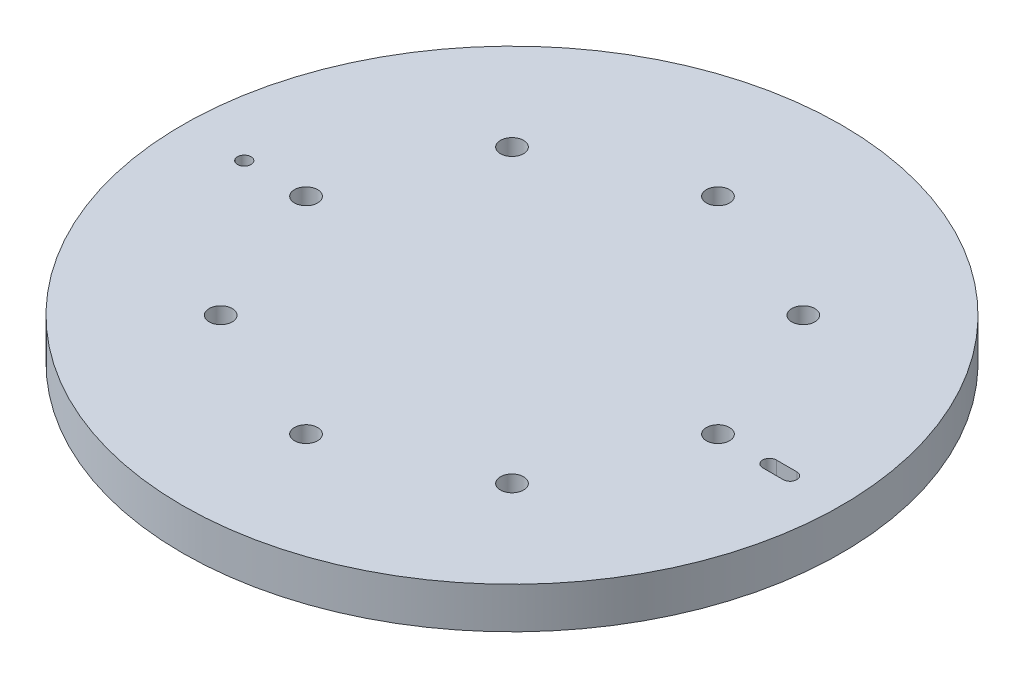
SolidWorks part; units mm, degrees
ref_plane "Front Plane" through (0, 0, 0) normal (0, 0, 1) x (1, 0, 0)
ref_plane "Top Plane" through (0, 0, 0) normal (0, 1, 0) x (1, 0, 0)
ref_plane "Right Plane" through (0, 0, 0) normal (1, 0, 0) x (0, 0, -1)
sketch "Sketch1" plane through (0, 0, 0) normal (1, 0, 0) x (0, 0, -1)
  line L0 (0, 0) -> (101.6, 0)
  line L1 (101.6, 0) -> (101.6, 12.7)
  line L2 (101.6, 12.7) -> (0, 12.7)
  line L3 (0, 12.7) -> (0, 0)
  line L4 (0, 46.9) -> (0, -34.9) construction
  dimension "D1" = 12.7
  dimension "D2" = 101.6
revolve "Revolve1" add sketch "Sketch1" angle 360 about L4
sketch "Sketch2" plane through (0, 12.7, 0) normal (0, 1, 0) x (1, 0, 0)
  line L0 (0, -101.6) -> (0, 101.6) construction
  line L1 (-50.1612, 63.5) -> (50.1612, 63.5) construction
  circle A0 centre (0, 0) radius 101.6 construction
  circle A1 centre (0, 63.5) radius 3.5687
  circle A2 centre (44.9013, 44.9013) radius 3.5687
  circle A3 centre (63.5, 0) radius 3.5687
  circle A4 centre (44.9013, -44.9013) radius 3.5687
  circle A5 centre (0, -63.5) radius 3.5687
  circle A6 centre (-44.9013, -44.9013) radius 3.5687
  circle A7 centre (-63.5, 0) radius 3.5687
  circle A8 centre (-44.9013, 44.9013) radius 3.5687
  point P7 (0, 0)
  point P10 (0, 63.5)
  point P28 (0, 0)
  dimension "D2" = 7.1374
  dimension "D1" = 63.5
  dimension "D3" = 8
extrude "Cut-Extrude1" cut sketch "Sketch2" against normal through all both and the other way through all
sketch "Sketch3" plane through (0, 12.7, 0) normal (0, 1, 0) x (1, 0, 0)
  line L0 (-101.6, 0) -> (101.6, 0) construction
  line L2 (79.375, -2.0955) -> (85.725, -2.0955)
  line L4 (79.375, 2.0955) -> (85.725, 2.0955)
  line L6 (79.375, -2.0955) -> (85.725, 2.0955) construction
  line L7 (79.375, 2.0955) -> (85.725, -2.0955) construction
  circle A0 centre (0, 0) radius 101.6 construction
  circle A1 centre (-82.55, 0) radius 2.0955
  arc A2 (79.375, 2.0955) -> (79.375, -2.0955) centre (79.375, 0) ccw
  arc A3 (85.725, -2.0955) -> (85.725, 2.0955) centre (85.725, 0) ccw
  point P7 (0, 0)
  point P10 (82.55, 0)
  point P18 (79.375, -2.0955)
  point P19 (79.375, 2.0955)
  dimension "D2" = 4.191
  dimension "D4" = 4.191
  dimension "D1" = 82.55
  dimension "D3" = 6.35
extrude "Cut-Extrude4" cut sketch "Sketch3" against normal blind 31.75
